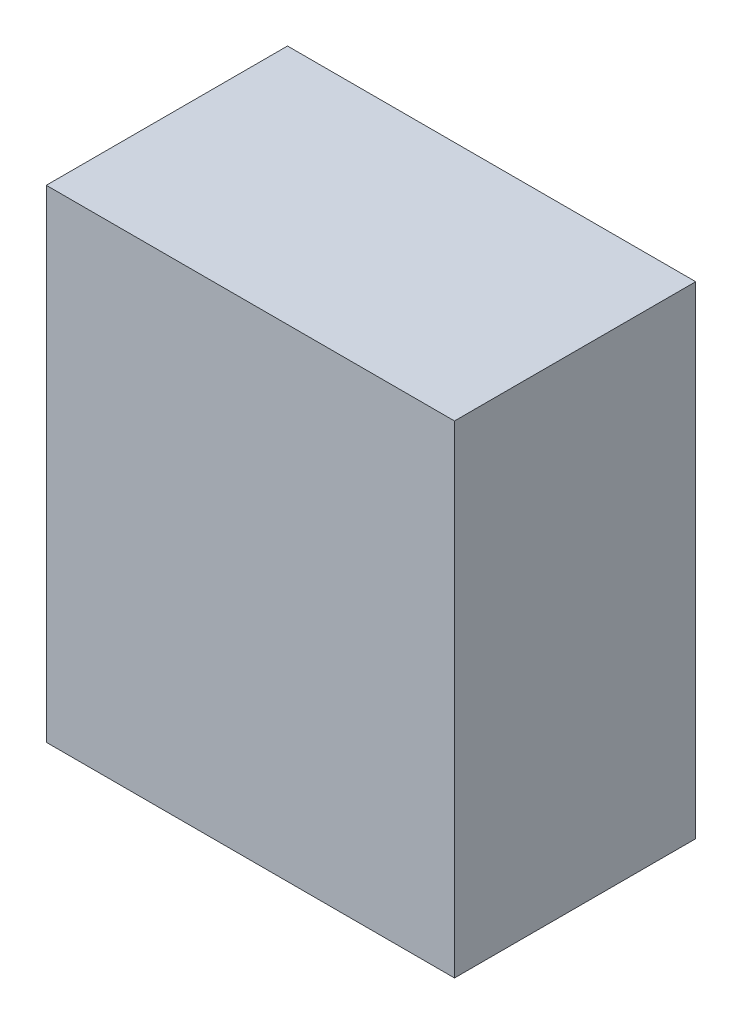
SolidWorks part; units mm, degrees
ref_plane "Front Plane" through (0, 0, 0) normal (0, 0, 1) x (1, 0, 0)
ref_plane "Top Plane" through (0, 0, 0) normal (0, 1, 0) x (1, 0, 0)
ref_plane "Right Plane" through (0, 0, 0) normal (1, 0, 0) x (0, 0, -1)
sketch "Sketch1" plane through (0, 0, 0) normal (0, 0, 1) x (1, 0, 0)
  line L0 (-11.8404, -6.9967) -> (-11.8404, 9.0033)
  line L1 (-11.8404, 9.0033) -> (-14.8404, 9.0033)
  line L2 (-14.8404, 9.0033) -> (-14.8404, -9.9967)
  line L3 (-14.8404, -9.9967) -> (7.1596, -9.9967)
  line L4 (7.1596, -9.9967) -> (7.1596, 16.0033)
  line L5 (7.1596, 16.0033) -> (-14.8404, 16.0033)
  line L6 (-14.8404, 16.0033) -> (-14.8404, 13.0033)
  line L7 (-14.8404, 13.0033) -> (4.1596, 13.0033)
  line L8 (4.1596, 13.0033) -> (4.1596, -6.9967)
  line L9 (4.1596, -6.9967) -> (-11.8404, -6.9967)
  dimension "D1" = 3
  dimension "D2" = 3
  dimension "D3" = 3
  dimension "D4" = 3
  dimension "D5" = 19
  dimension "D6" = 16
  dimension "D7" = 16
  dimension "D8" = 20
extrude "Boss-Extrude1" add sketch "Sketch1" along normal blind 10
sketch "Sketch2" plane through (0, 0, 10) normal (0, 0, 1) x (1, 0, 0)
  line L0 (-14.8404, 16.0033) -> (7.1596, 16.0033)
  line L1 (7.1596, 16.0033) -> (7.1596, -9.9967)
  line L2 (7.1596, -9.9967) -> (-14.8404, -9.9967)
  line L3 (-14.8404, -9.9967) -> (-14.8404, 16.0033)
extrude "Boss-Extrude2" add sketch "Sketch2" along normal blind 3
